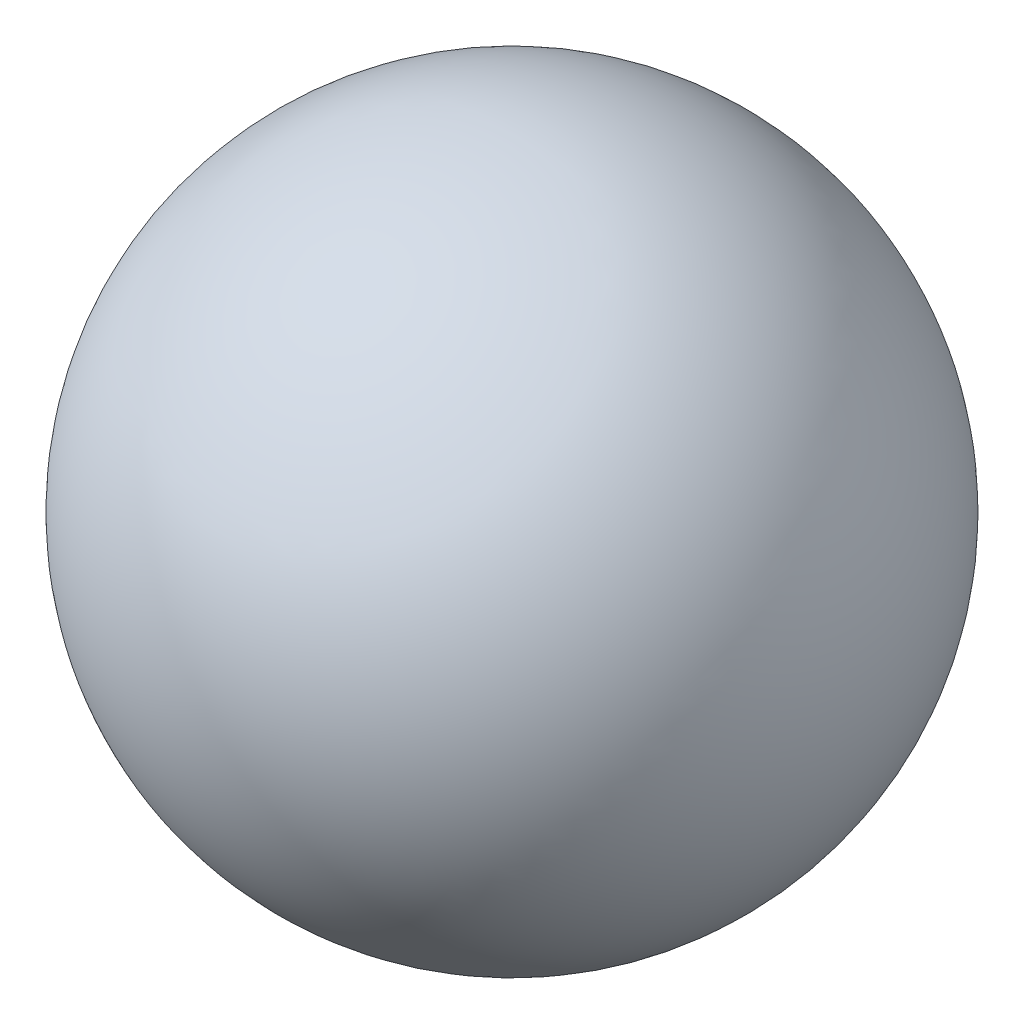
SolidWorks part; units mm, degrees
material "1023 Carbon Steel Sheet (SS)"
ref_plane "Front Plane" through (0, 0, 0) normal (0, 0, 1) x (1, 0, 0)
ref_plane "Top Plane" through (0, 0, 0) normal (0, 1, 0) x (1, 0, 0)
ref_plane "Right Plane" through (0, 0, 0) normal (1, 0, 0) x (0, 0, -1)
sketch "Sketch1" plane through (0, 0, 0) normal (0, 0, 1) x (1, 0, 0)
  line L0 (-5, 0) -> (5, 0)
  arc A1 (-5, 0) -> (5, 0) centre (0, 0) cw
  point P3 (0, 0)
  dimension "D1" = 10
revolve "Revolve1" add sketch "Sketch1" angle 360 about L0
sketch "Sketch2" plane through (0, 0, 0) normal (0, 0, 1) x (1, 0, 0)
  circle A0 centre (0, 0) radius 2
  dimension "D1" = 4
extrude "Cut-Extrude1" cut sketch "Sketch2" against normal blind 10
ref_plane "Plane1" through (0, 0, -4.2) normal (0, 0, 1) x (1, 0, 0)
sketch "Sketch3" plane through (0, 0, -4.2) normal (0, 0, 1) x (1, 0, 0)
  line L1 (-6.4854, -5.3192) -> (6.4854, -5.3192)
  line L2 (-6.4854, -5.3192) -> (-6.4854, 5.3192)
  line L3 (-6.4854, 5.3192) -> (6.4854, 5.3192)
  line L4 (6.4854, -5.3192) -> (6.4854, 5.3192)
  line L5 (-6.4854, -5.3192) -> (6.4854, 5.3192) construction
  line L6 (-6.4854, 5.3192) -> (6.4854, -5.3192) construction
  point P0 (0, 0)
extrude "Cut-Extrude2" cut sketch "Sketch3" against normal blind 10
